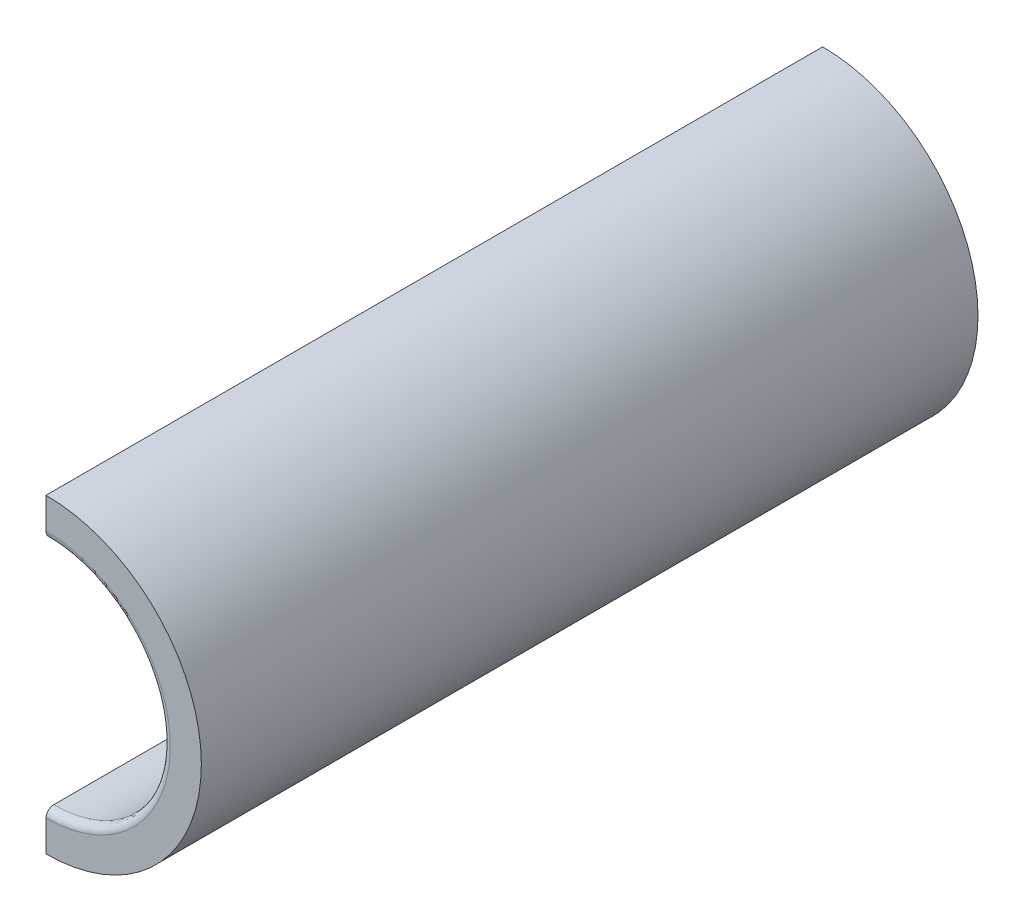
SolidWorks part; units mm, degrees
material "1.0037 (S235JR)"
ref_plane "E_Rechts" through (0, 0, 0) normal (0, 0, 1) x (1, 0, 0)
ref_plane "E_Oben" through (0, 0, 0) normal (0, 1, 0) x (1, 0, 0)
ref_plane "E_Vorne" through (0, 0, 0) normal (1, 0, 0) x (0, 0, -1)
sketch "Skizze1" plane through (0, 0, 0) normal (0, 0, 1) x (1, 0, 0)
  line L0 (0, 40) -> (0, 30)
  line L1 (0, -30) -> (0, -40)
  arc A0 (0, -40) -> (0, 40) centre (0, 0) ccw
  arc A1 (0, -30) -> (0, 30) centre (0, 0) ccw
extrude "Aufsatz-Linear austragen1" add sketch "Skizze1" along normal mid plane 200
fillet "Verrundung1" radius 2 2 edges at (30, 0, -100) (30, 0, 100)
